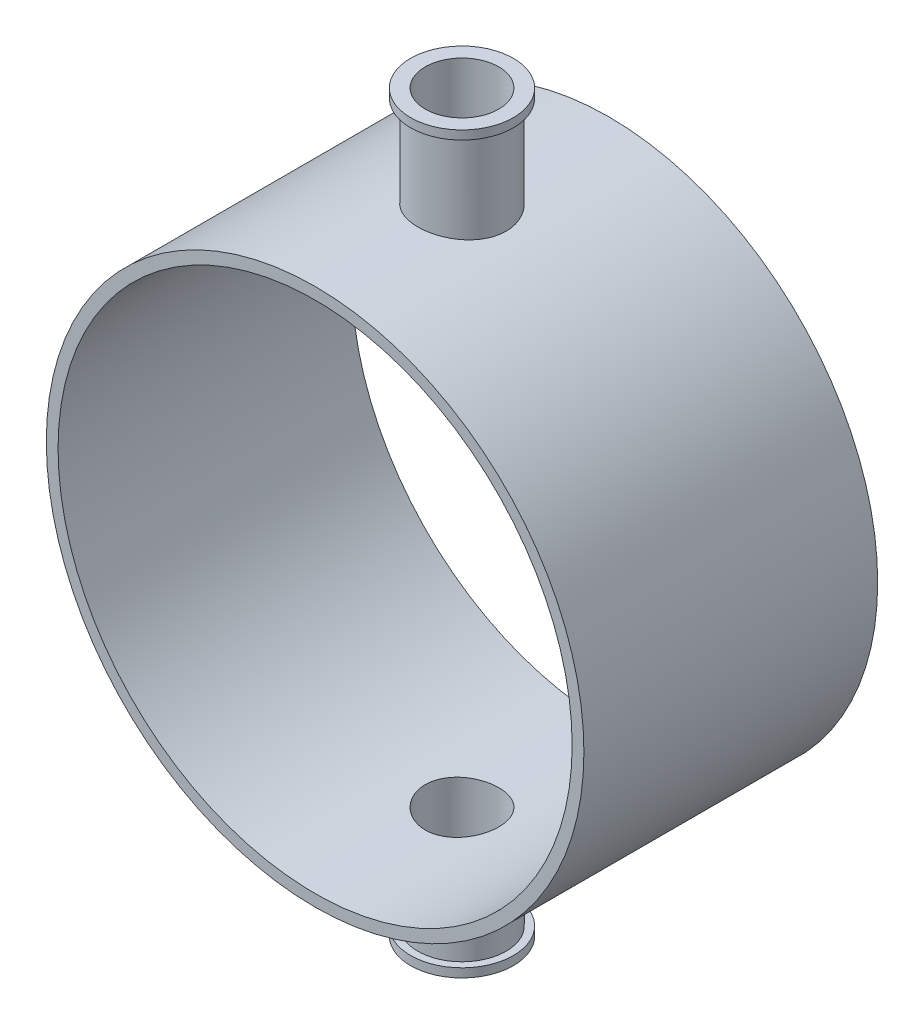
SolidWorks part; units mm, degrees
material "Steel Stainless 302"
ref_plane "Front Plane" through (0, 0, 0) normal (0, 0, 1) x (1, 0, 0)
ref_plane "Top Plane" through (0, 0, 0) normal (0, 1, 0) x (1, 0, 0)
ref_plane "Right Plane" through (0, 0, 0) normal (1, 0, 0) x (0, 0, -1)
sketch "Sketch1" plane through (0, 0, 0) normal (0, 0, 1) x (1, 0, 0)
  circle A0 centre (0, 0) radius 444.5
  circle A1 centre (0, 0) radius 464.82
  dimension "D1" = 889
  dimension "D2" = 929.64
extrude "Boss-Extrude1" add sketch "Sketch1" against normal blind 508
sketch "Sketch2" plane through (0, 0, 0) normal (0, 1, 0) x (1, 0, 0)
  line L0 (0, 0) -> (0, 508) construction
  line L1 (444.5, 508) -> (-444.5, 508) construction
  circle A0 centre (0, 254) radius 63.5
  circle A1 centre (0, 254) radius 63.5
  circle A2 centre (0, 254) radius 76.2
  dimension "D1" = 127
  dimension "D2" = 12.7
extrude "Boss-Extrude2" add sketch "Sketch2" along normal mid plane 1270 contours L0 A2 A0 | A2 L0 A1 | L0 A0 | A1 L0
sketch "Sketch3" plane through (0, 0, -508) normal (0, 0, -1) x (-1, 0, 0)
  circle A0 centre (0, 0) radius 444.5 construction
  circle A1 centre (0, 0) radius 444.5
extrude "Cut-Extrude1" cut sketch "Sketch3" against normal mid plane 1397
sketch "Sketch4" plane through (0, 635, 0) normal (0, 1, 0) x (1, 0, 0)
  circle A0 centre (0, 254) radius 63.5 construction
  circle A1 centre (0, 254) radius 63.5
extrude "Cut-Extrude2" cut sketch "Sketch4" against normal mid plane 3620.516
sketch "Sketch5" plane through (0, -635, 0) normal (0, -1, 0) x (1, 0, 0)
  circle A0 centre (0, -254) radius 88.9
  circle A2 centre (0, -254) radius 76.2
  circle A3 centre (0, -254) radius 76.2
  dimension "D1" = 177.8
  dimension "D2" = 0
extrude "Boss-Extrude3" add sketch "Sketch5" against normal blind 15.24
mirror "Mirror1" about plane through (0, 0, 0) normal (0, 1, 0) of "Boss-Extrude3"
